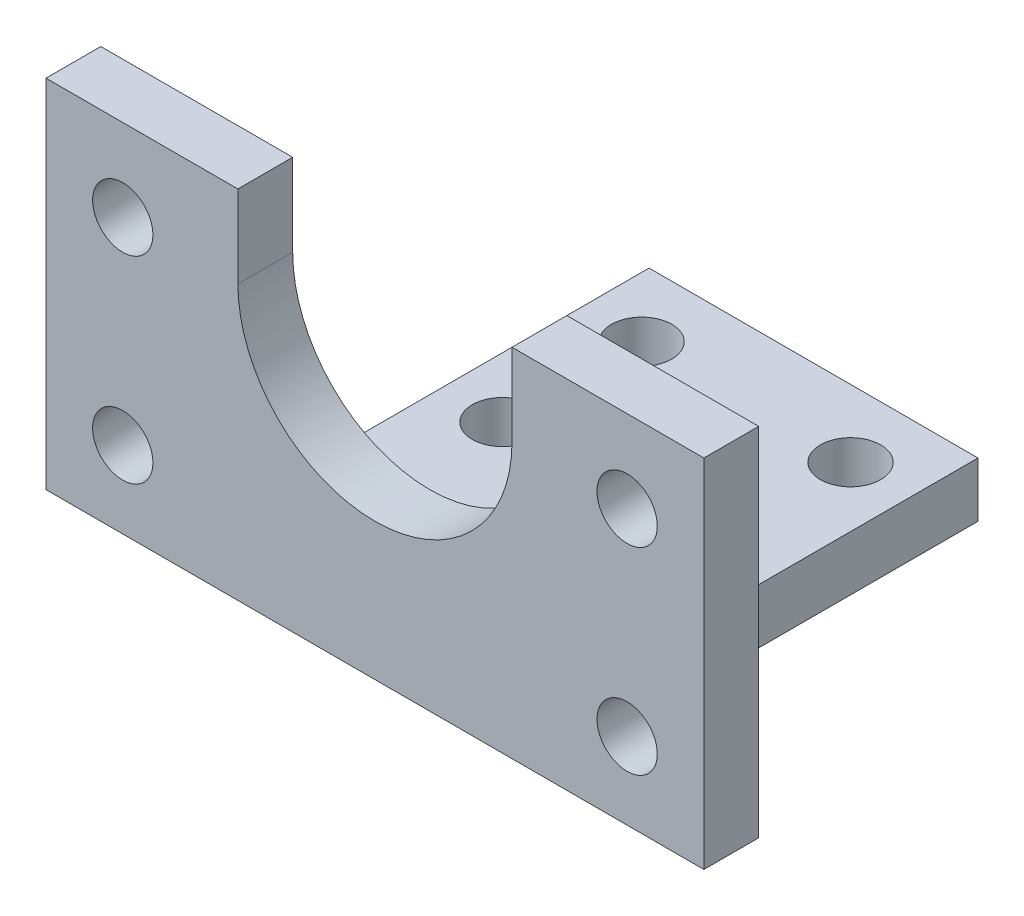
SolidWorks part; units mm, degrees
ref_plane "Front Plane" through (0, 0, 0) normal (0, 0, 1) x (1, 0, 0)
ref_plane "Top Plane" through (0, 0, 0) normal (0, 1, 0) x (1, 0, 0)
ref_plane "Right Plane" through (0, 0, 0) normal (1, 0, 0) x (0, 0, -1)
sketch "Sketch1" plane through (0, 0, 0) normal (0, 0, 1) x (1, 0, 0)
  line L0 (30, 32.5) -> (30, 0) construction
  line L1 (0, 0) -> (60, 0)
  line L2 (0, 0) -> (0, 32.5)
  line L3 (0, 32.5) -> (60, 32.5)
  line L4 (60, 0) -> (60, 32.5)
  line L5 (0, 16.25) -> (60, 16.25) construction
  line L6 (42.5, 25) -> (42.5, 32.5)
  line L7 (7, 25) -> (53, 25) construction
  line L8 (7, 25) -> (7, 7) construction
  line L9 (7, 7) -> (53, 7) construction
  line L10 (53, 25) -> (53, 7) construction
  line L11 (17.5, 25) -> (17.5, 32.5)
  arc A0 (17.5, 25) -> (42.5, 25) centre (30, 25) ccw
  circle A1 centre (53, 25) radius 2.75
  circle A2 centre (53, 7) radius 2.75
  circle A3 centre (7, 7) radius 2.75
  circle A4 centre (7, 25) radius 2.75
  dimension "D3" = 25
  dimension "D6" = 5.5
  dimension "D8" = 20
  dimension "D1" = 32.5
  dimension "D2" = 60
  dimension "D4" = 18
  dimension "D5" = 46
  dimension "D7" = 7
extrude "Boss-Extrude1" add sketch "Sketch1" along normal blind 5 contours A0 L11 L3 L2 L1 L4 L6 A4 A3 A2 A1
sketch "Sketch2" plane through (0, 0, 0) normal (0, -1, 0) x (1, 0, 0)
  line L1 (0, 5) -> (60, 5) construction
  line L8 (45, 5) -> (15, 5)
  line L9 (30, 9.2263) -> (30, -4.7477) construction
  line L10 (15, 5) -> (15, -35)
  line L11 (15, -35) -> (45, -35)
  line L12 (45, -35) -> (45, 5)
  line L13 (15, -22.5) -> (45, -22.5) construction
  line L14 (20.475, -16.15) -> (39.525, -16.15) construction
  line L15 (20.475, -16.15) -> (20.475, -28.85) construction
  line L16 (20.475, -28.85) -> (39.525, -28.85) construction
  line L17 (39.525, -16.15) -> (39.525, -28.85) construction
  line L18 (0, 0) -> (60, 0) construction
  circle A0 centre (20.475, -16.15) radius 2.75
  circle A1 centre (39.525, -16.15) radius 2.75
  circle A2 centre (39.525, -28.85) radius 2.75
  circle A3 centre (20.475, -28.85) radius 2.75
  point P13 (30, 5)
  dimension "D6" = 5.5
  dimension "D1" = 30
  dimension "D2" = 40
  dimension "D3" = 12.7
  dimension "D4" = 19.05
  dimension "D5" = 22.5
extrude "Boss-Extrude2" add sketch "Sketch2" against normal blind 5
